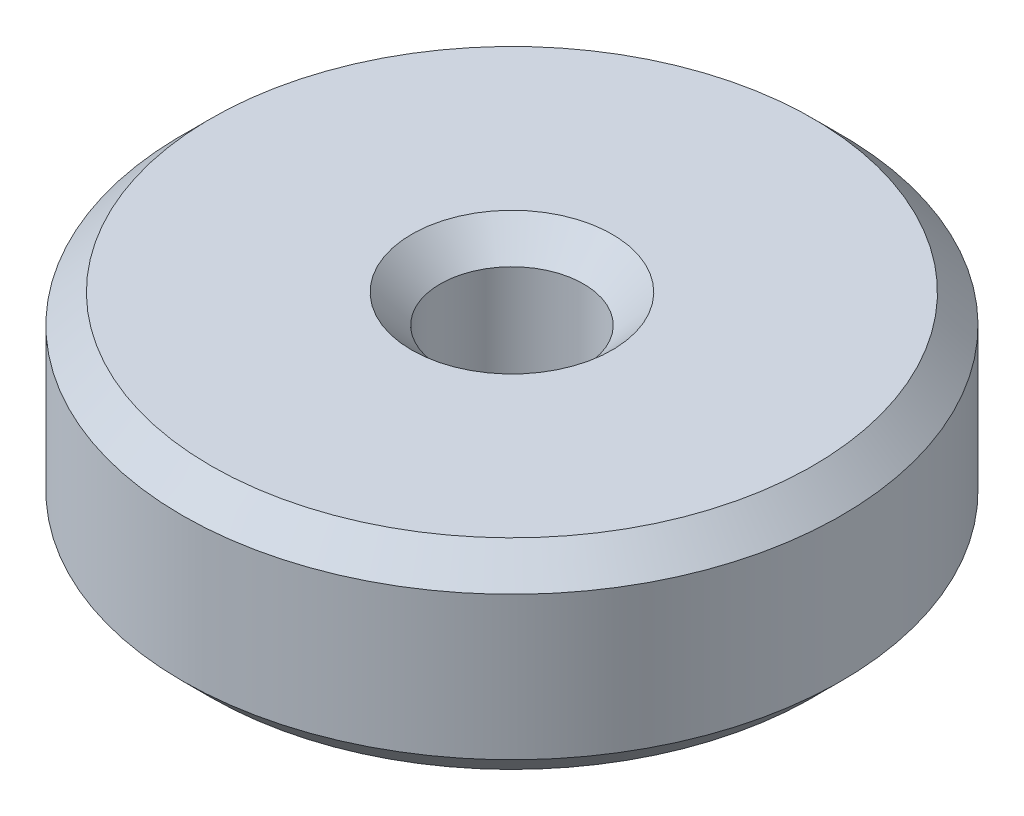
SolidWorks part; units mm, degrees
ref_plane "Front Plane" through (0, 0, 0) normal (0, 0, 1) x (1, 0, 0)
ref_plane "Top Plane" through (0, 0, 0) normal (0, 1, 0) x (1, 0, 0)
ref_plane "Right Plane" through (0, 0, 0) normal (1, 0, 0) x (0, 0, -1)
sketch "Sketch1" plane through (0, 0, 0) normal (0, 1, 0) x (1, 0, 0)
  circle A0 centre (0, 0) radius 11.5
  circle A1 centre (0, 0) radius 2.5
  dimension "D1" = 23
  dimension "D2" = 5
extrude "Boss-Extrude1" add sketch "Sketch1" along normal blind 7
chamfer "Chamfer1" distance 1 angle 45 4 edges at (0, 0, 11.5) (0, 7, 11.5) (0, 0, 2.5) (0, 7, 2.5)
